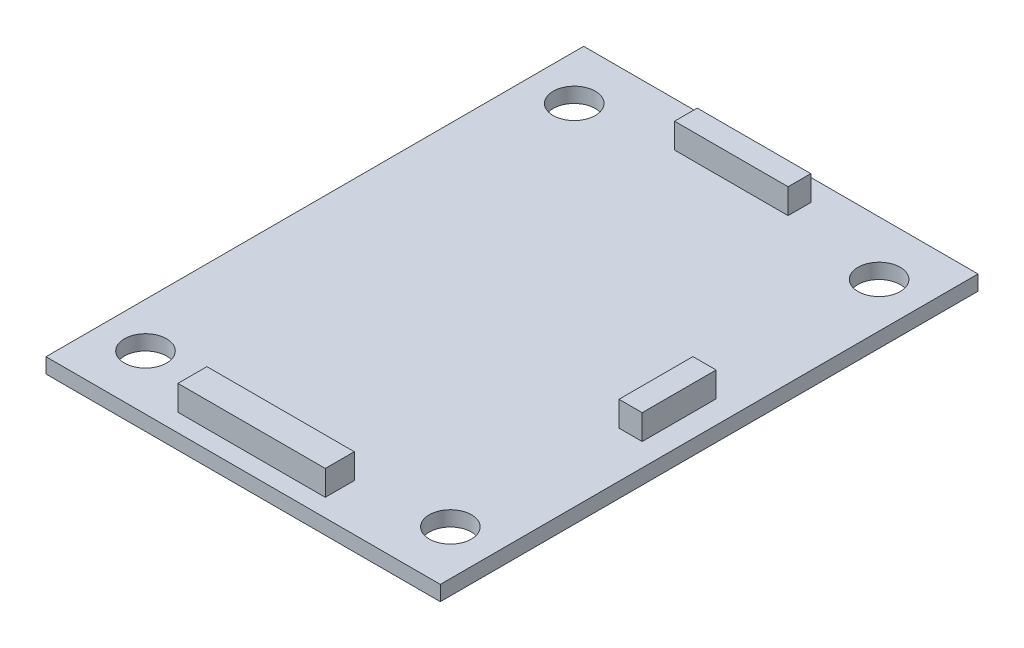
SolidWorks part; units mm, degrees
ref_plane "Front Plane" through (0, 0, 0) normal (0, 0, 1) x (1, 0, 0)
ref_plane "Top Plane" through (0, 0, 0) normal (0, 1, 0) x (1, 0, 0)
ref_plane "Right Plane" through (0, 0, 0) normal (1, 0, 0) x (0, 0, -1)
sketch "Sketch1" plane through (0, 0, 0) normal (0, 1, 0) x (1, 0, 0)
  line L1 (-3.5725, 38.5993) -> (27.946, 38.5993)
  line L2 (-3.5725, 38.5993) -> (-3.5725, -4.3805)
  line L3 (-3.5725, -4.3805) -> (27.946, -4.3805)
  line L4 (27.946, 38.5993) -> (27.946, -4.3805)
  circle A0 centre (0, 0) radius 1.685
  circle A1 centre (24.37, 0) radius 1.685
  circle A2 centre (24.37, 34.27) radius 1.685
  circle A3 centre (0, 34.27) radius 1.685
  dimension "D1" = 3.37
  dimension "D2" = 2
  dimension "D3" = 2
extrude "Boss-Extrude1" add sketch "Sketch1" along normal blind 1.2
sketch "Sketch2" plane through (0, 1.2, 0) normal (0, 1, 0) x (1, 0, 0)
  line L1 (7.244, 36.8611) -> (16.3186, 36.8611)
  line L2 (7.244, 36.8611) -> (7.244, 35.0462)
  line L3 (7.244, 35.0462) -> (16.3186, 35.0462)
  line L4 (16.3186, 36.8611) -> (16.3186, 35.0462)
  line L5 (24.2734, 19.4842) -> (26.1269, 19.4842)
  line L6 (24.2734, 19.4842) -> (24.2734, 13.5761)
  line L7 (24.2734, 13.5761) -> (26.1269, 13.5761)
  line L8 (26.1269, 19.4842) -> (26.1269, 13.5761)
  line L9 (5.5449, -0.6344) -> (17.3226, -0.6344)
  line L10 (5.5449, -0.6344) -> (5.5449, -2.9513)
  line L11 (5.5449, -2.9513) -> (17.3226, -2.9513)
  line L12 (17.3226, -0.6344) -> (17.3226, -2.9513)
extrude "Boss-Extrude2" add sketch "Sketch2" along normal blind 2
